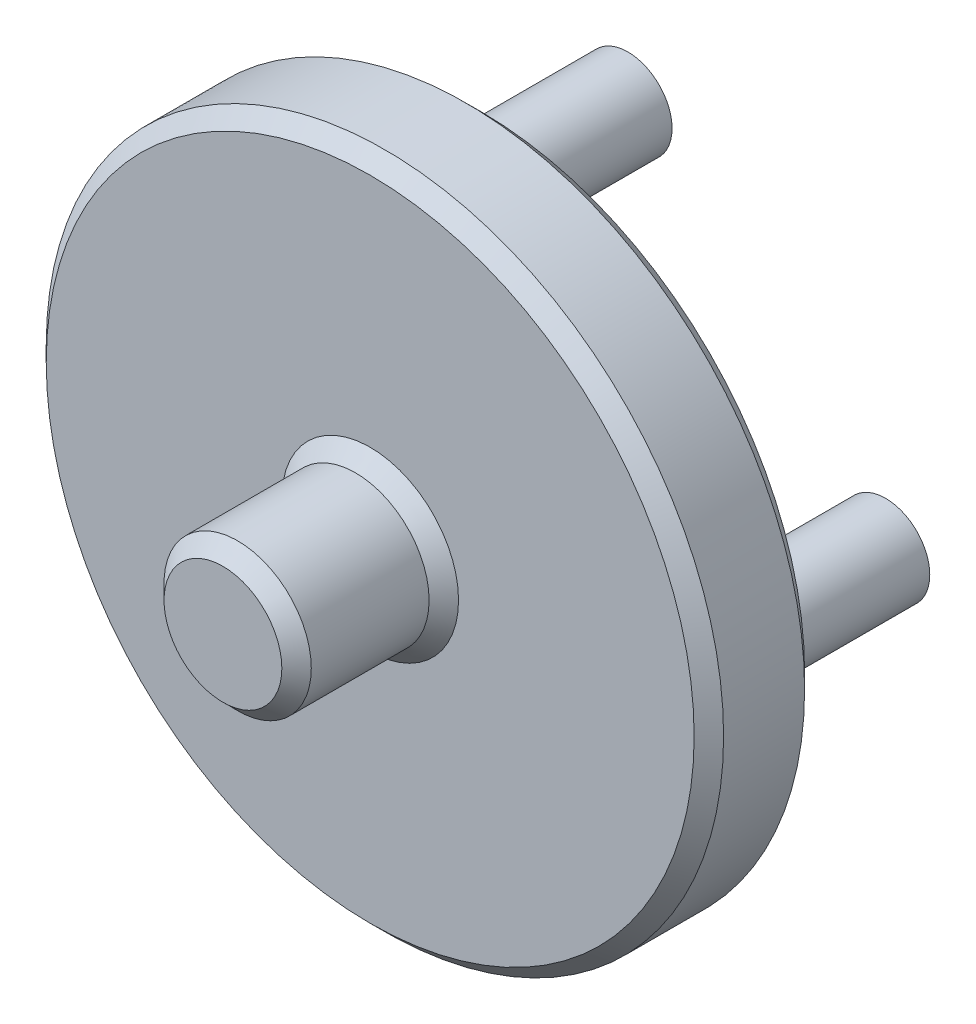
SolidWorks part; units mm, degrees
material "1023 Carbon Steel Sheet (SS)"
ref_plane "Front Plane" through (0, 0, 0) normal (0, 0, 1) x (1, 0, 0)
ref_plane "Top Plane" through (0, 0, 0) normal (0, 1, 0) x (1, 0, 0)
ref_plane "Right Plane" through (0, 0, 0) normal (1, 0, 0) x (0, 0, -1)
sketch "Sketch1" plane through (0, 0, 0) normal (0, 0, 1) x (1, 0, 0)
  circle A0 centre (0, 0) radius 23
  dimension "D1" = 46
extrude "Boss-Extrude1" add sketch "Sketch1" along normal blind 7.5
sketch "Sketch2" plane through (0, 0, 0) normal (0, 0, 1) x (1, 0, 0)
  circle A0 centre (0, 0) radius 17.5 construction
  circle A1 centre (0, 17.5) radius 3
  circle A2 centre (17.5, 0) radius 3
  circle A3 centre (0, -17.5) radius 3
  circle A4 centre (-17.5, 0) radius 3
  point P14 (0, 0)
  dimension "D1" = 35
  dimension "D2" = 6
extrude "Boss-Extrude2" add sketch "Sketch2" against normal blind 10
sketch "Sketch3" plane through (0, 0, 7.5) normal (0, 0, 1) x (1, 0, 0)
  circle A0 centre (0, 0) radius 5
  dimension "D1" = 10
extrude "Boss-Extrude3" add sketch "Sketch3" along normal blind 10
chamfer "Chamfer1" distance 1 angle 45 8 edges at (5, 0, 17.5) (5, 0, 7.5) (3, -17.5, 0) (-14.5, 0, 0) (3, 17.5, 0) (20.5, 0, 0) (23, 0, 0) (23, 0, 7.5)
